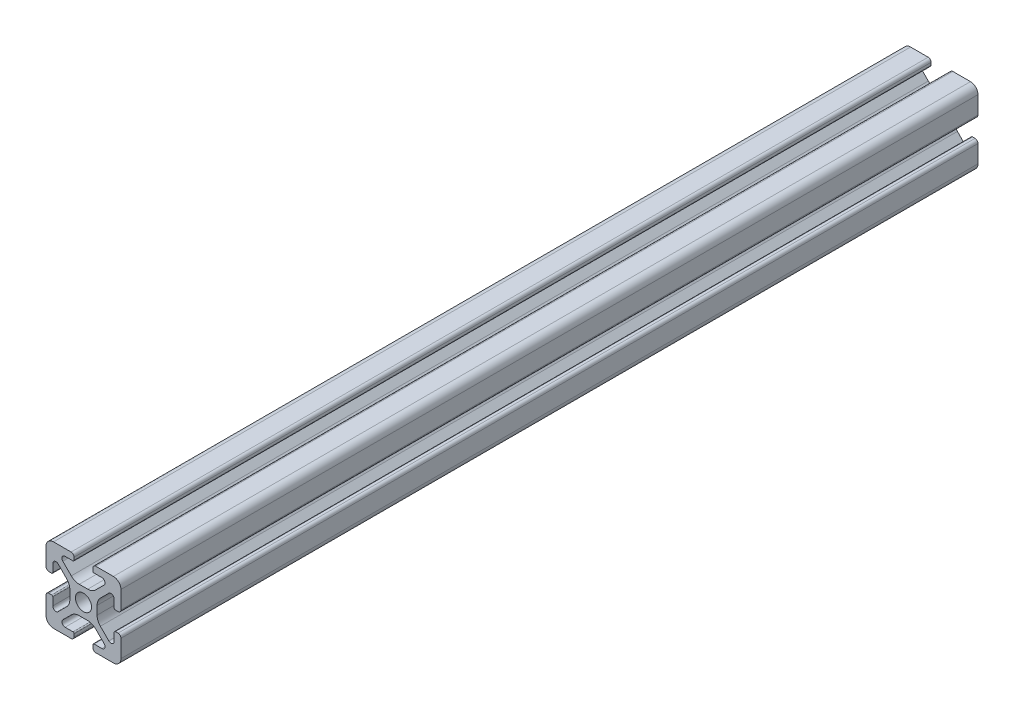
SolidWorks part; units mm, degrees
ref_plane "Front Plane" through (0, 0, 0) normal (0, 0, 1) x (1, 0, 0)
ref_plane "Top Plane" through (0, 0, 0) normal (0, 1, 0) x (1, 0, 0)
ref_plane "Right Plane" through (0, 0, 0) normal (1, 0, 0) x (0, 0, -1)
sketch "Sketch1" plane through (0, 0, 0) normal (0, 0, 1) x (1, 0, 0)
  line L2 (-9.9949, 7.9883) -> (-9.9949, 3.2893)
  line L3 (-7.9883, 9.9949) -> (-3.2893, 9.9949)
  line L4 (-2.5019, 9.2075) -> (-2.5019, 8.4963)
  line L5 (-2.8067, 8.1915) -> (-4.9149, 8.1915)
  line L6 (-5.5076, 6.7606) -> (-3.2528, 4.5058)
  line L7 (-6.7606, 5.5076) -> (-4.5058, 3.2528)
  line L8 (-8.1915, 4.9149) -> (-8.1915, 2.8067)
  line L9 (-8.4963, 2.5019) -> (-9.2075, 2.5019)
  line L11 (-1.1334, 3.6279) -> (1.1334, 3.6279)
  line L12 (-3.6279, 1.1334) -> (-3.6279, -1.1334)
  line L13 (8.4963, 2.5019) -> (9.2075, 2.5019)
  line L14 (8.1915, 4.9149) -> (8.1915, 2.8067)
  line L15 (9.9949, 7.9883) -> (9.9949, 3.2893)
  line L16 (7.9883, 9.9949) -> (3.2893, 9.9949)
  line L17 (2.5019, 9.2075) -> (2.5019, 8.4963)
  line L18 (2.8067, 8.1915) -> (4.9149, 8.1915)
  line L19 (3.6279, 1.1334) -> (3.6279, -1.1334)
  line L20 (5.5076, 6.7606) -> (3.2528, 4.5058)
  line L21 (6.7606, 5.5076) -> (4.5058, 3.2528)
  line L22 (-8.4963, -2.5019) -> (-9.2075, -2.5019)
  line L23 (-8.1915, -4.9149) -> (-8.1915, -2.8067)
  line L24 (-6.7606, -5.5076) -> (-4.5058, -3.2528)
  line L25 (-5.5076, -6.7606) -> (-3.2528, -4.5058)
  line L26 (-2.8067, -8.1915) -> (-4.9149, -8.1915)
  line L27 (-2.5019, -9.2075) -> (-2.5019, -8.4963)
  line L28 (-7.9883, -9.9949) -> (-3.2893, -9.9949)
  line L29 (-9.9949, -7.9883) -> (-9.9949, -3.2893)
  line L30 (9.9949, -7.9883) -> (9.9949, -3.2893)
  line L31 (7.9883, -9.9949) -> (3.2893, -9.9949)
  line L32 (2.5019, -9.2075) -> (2.5019, -8.4963)
  line L33 (2.8067, -8.1915) -> (4.9149, -8.1915)
  line L34 (5.5076, -6.7606) -> (3.2528, -4.5058)
  line L35 (6.7606, -5.5076) -> (4.5058, -3.2528)
  line L36 (8.1915, -4.9149) -> (8.1915, -2.8067)
  line L37 (8.4963, -2.5019) -> (9.2075, -2.5019)
  line L38 (-1.1334, -3.6279) -> (1.1334, -3.6279)
  circle A0 centre (0, 0) radius 2.1463
  arc A1 (-9.9949, 7.9883) -> (-7.9883, 9.9949) centre (-7.9883, 7.9883) cw
  arc A2 (-6.7606, 5.5076) -> (-8.1915, 4.9149) centre (-7.3533, 4.9149) ccw
  arc A3 (-4.9149, 8.1915) -> (-5.5076, 6.7606) centre (-4.9149, 7.3533) ccw
  arc A4 (-3.2893, 9.9949) -> (-2.5019, 9.2075) centre (-3.2893, 9.2075) cw
  arc A5 (-9.9949, 3.2893) -> (-9.2075, 2.5019) centre (-9.2075, 3.2893) ccw
  arc A6 (-8.1915, 2.8067) -> (-8.4963, 2.5019) centre (-8.4963, 2.8067) cw
  arc A7 (-2.5019, 8.4963) -> (-2.8067, 8.1915) centre (-2.8067, 8.4963) cw
  arc A8 (-1.1334, 3.6279) -> (-3.2528, 4.5058) centre (-1.1334, 6.6251) cw
  arc A9 (-3.6279, 1.1334) -> (-4.5058, 3.2528) centre (-6.6251, 1.1334) ccw
  arc A10 (8.1915, 2.8067) -> (8.4963, 2.5019) centre (8.4963, 2.8067) ccw
  arc A11 (9.9949, 3.2893) -> (9.2075, 2.5019) centre (9.2075, 3.2893) cw
  arc A12 (9.9949, 7.9883) -> (7.9883, 9.9949) centre (7.9883, 7.9883) ccw
  arc A13 (3.2893, 9.9949) -> (2.5019, 9.2075) centre (3.2893, 9.2075) ccw
  arc A14 (2.5019, 8.4963) -> (2.8067, 8.1915) centre (2.8067, 8.4963) ccw
  arc A15 (1.1334, 3.6279) -> (3.2528, 4.5058) centre (1.1334, 6.6251) ccw
  arc A16 (3.6279, 1.1334) -> (4.5058, 3.2528) centre (6.6251, 1.1334) cw
  arc A17 (6.7606, 5.5076) -> (8.1915, 4.9149) centre (7.3533, 4.9149) cw
  arc A18 (4.9149, 8.1915) -> (5.5076, 6.7606) centre (4.9149, 7.3533) cw
  arc A19 (-3.6279, -1.1334) -> (-4.5058, -3.2528) centre (-6.6251, -1.1334) cw
  arc A20 (-1.1334, -3.6279) -> (-3.2528, -4.5058) centre (-1.1334, -6.6251) ccw
  arc A21 (-2.5019, -8.4963) -> (-2.8067, -8.1915) centre (-2.8067, -8.4963) ccw
  arc A22 (-8.1915, -2.8067) -> (-8.4963, -2.5019) centre (-8.4963, -2.8067) ccw
  arc A23 (-9.9949, -3.2893) -> (-9.2075, -2.5019) centre (-9.2075, -3.2893) cw
  arc A24 (-3.2893, -9.9949) -> (-2.5019, -9.2075) centre (-3.2893, -9.2075) ccw
  arc A25 (-4.9149, -8.1915) -> (-5.5076, -6.7606) centre (-4.9149, -7.3533) cw
  arc A26 (-6.7606, -5.5076) -> (-8.1915, -4.9149) centre (-7.3533, -4.9149) cw
  arc A27 (-9.9949, -7.9883) -> (-7.9883, -9.9949) centre (-7.9883, -7.9883) ccw
  arc A28 (9.9949, -7.9883) -> (7.9883, -9.9949) centre (7.9883, -7.9883) cw
  arc A29 (6.7606, -5.5076) -> (8.1915, -4.9149) centre (7.3533, -4.9149) ccw
  arc A30 (4.9149, -8.1915) -> (5.5076, -6.7606) centre (4.9149, -7.3533) ccw
  arc A31 (3.2893, -9.9949) -> (2.5019, -9.2075) centre (3.2893, -9.2075) cw
  arc A32 (9.9949, -3.2893) -> (9.2075, -2.5019) centre (9.2075, -3.2893) ccw
  arc A33 (8.1915, -2.8067) -> (8.4963, -2.5019) centre (8.4963, -2.8067) cw
  arc A34 (2.5019, -8.4963) -> (2.8067, -8.1915) centre (2.8067, -8.4963) cw
  arc A35 (1.1334, -3.6279) -> (3.2528, -4.5058) centre (1.1334, -6.6251) cw
  arc A36 (3.6279, -1.1334) -> (4.5058, -3.2528) centre (6.6251, -1.1334) ccw
extrude "Boss-Extrude1" add sketch "Sketch1" along normal mid plane 228.6
